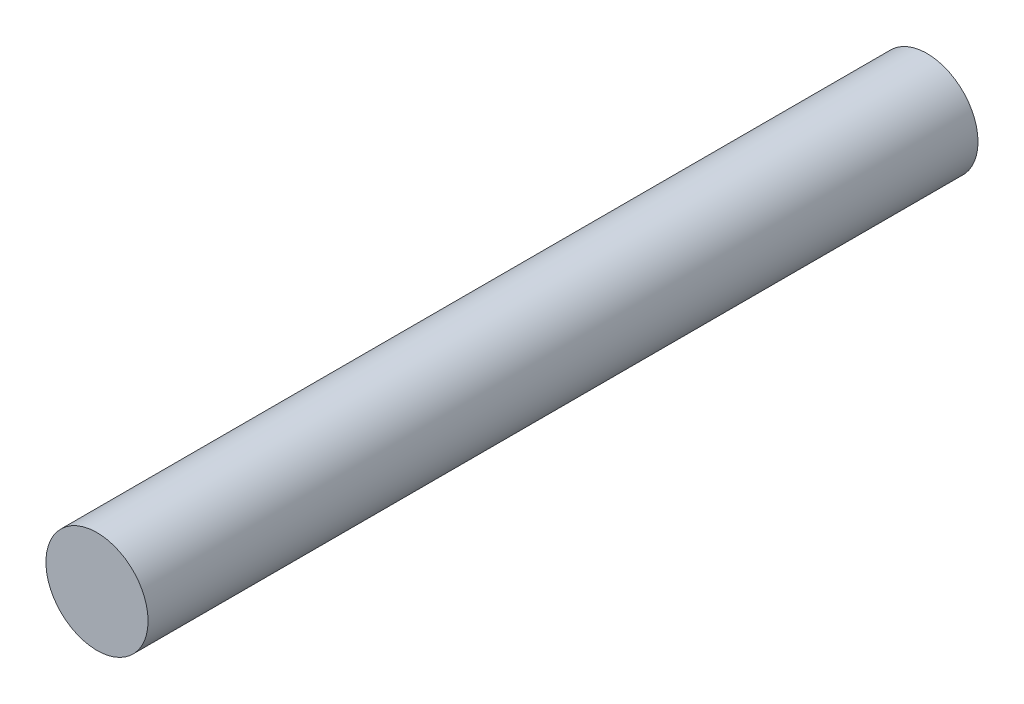
SolidWorks part; units mm, degrees
ref_plane "Front Plane" through (0, 0, 0) normal (0, 0, 1) x (1, 0, 0)
ref_plane "Top Plane" through (0, 0, 0) normal (0, 1, 0) x (1, 0, 0)
ref_plane "Right Plane" through (0, 0, 0) normal (1, 0, 0) x (0, 0, -1)
sketch "Sketch1" plane through (0, 0, 0) normal (0, 0, 1) x (1, 0, 0)
  circle A0 centre (0, 0) radius 4
extrude "Boss-Extrude1" add sketch "Sketch1" along normal blind 65
